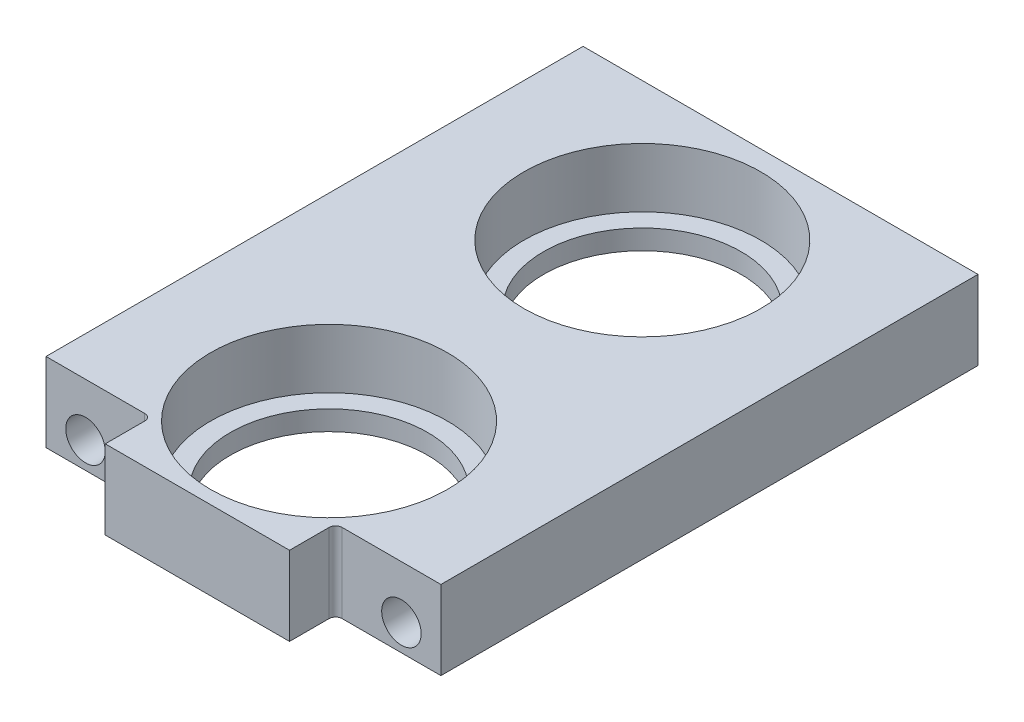
SolidWorks part; units mm, degrees
material "6061 合金"
ref_plane "前视基准面" through (0, 0, 0) normal (0, 0, 1) x (1, 0, 0)
ref_plane "上视基准面" through (0, 0, 0) normal (0, 1, 0) x (1, 0, 0)
ref_plane "右视基准面" through (0, 0, 0) normal (1, 0, 0) x (0, 0, -1)
sketch "草图1" plane through (0, 0, 0) normal (0, 1, 0) x (1, 0, 0)
  line L1 (-15, 22.15) -> (15, 22.15)
  line L2 (-15, 22.15) -> (-15, -22.15)
  line L3 (-15, -22.15) -> (15, -22.15)
  line L4 (15, 22.15) -> (15, -22.15)
  line L5 (-15, 22.15) -> (15, -22.15) construction
  line L6 (-15, -22.15) -> (15, 22.15) construction
  point P0 (0, 0)
  dimension "D1" = 30
  dimension "D2" = 44.3
extrude "凸台-拉伸1" add sketch "草图1" along normal blind 6
sketch "草图2" plane through (0, 6, 0) normal (0, 1, 0) x (1, 0, 0)
  line L0 (0, 22.15) -> (0, -22.15) construction
  line L1 (15, 22.15) -> (-15, 22.15) construction
  line L2 (-15, -22.15) -> (15, -22.15) construction
  circle A0 centre (0, 11.65) radius 9
  circle A1 centre (0, -12.15) radius 9
  dimension "D1" = 18
  dimension "D2" = 10.5
  dimension "D3" = 23.8
extrude "切除-拉伸1" cut sketch "草图2" against normal blind 4.5
sketch "草图3" plane through (0, 1.5, 0) normal (0, 1, 0) x (1, 0, 0)
  circle A0 centre (0, 11.65) radius 7.5
  circle A1 centre (0, -12.15) radius 7.5
  dimension "D1" = 15
extrude "切除-拉伸2" cut sketch "草图3" against normal blind 4.5
sketch "草图5" plane through (0, 6, 0) normal (0, 1, 0) x (1, 0, 0)
  line L0 (0, 0) -> (0, -22.15) construction
  line L1 (-15, -22.15) -> (15, -22.15) construction
  line L2 (-7, -22.15) -> (7, -22.15) construction
  line L3 (7, -22.15) -> (7, -18.65)
  line L4 (7, -18.65) -> (15, -18.65)
  line L5 (15, -22.15) -> (15, 22.15) construction
  line L6 (15, -18.65) -> (15, -22.15)
  line L7 (15, -22.15) -> (7, -22.15)
  line L8 (-15, -18.65) -> (-15, -22.15)
  line L9 (-7, -18.65) -> (-15, -18.65)
  line L10 (-7, -22.15) -> (-7, -18.65)
  line L11 (-15, -22.15) -> (-7, -22.15)
  dimension "D1" = 14
  dimension "D2" = 3.5
extrude "切除-拉伸3" cut sketch "草图5" against normal blind 10
fillet "圆角1" radius 0.5 2 edges at (-7, 3, 18.65) (7, 3, 18.65)
sketch "草图6" plane through (0, 0, 18.65) normal (0, 0, 1) x (1, 0, 0)
  line L0 (-8, 6) -> (-8, 0) construction
  line L1 (-7.5, 6) -> (-15, 6) construction
  line L2 (-7.5, 0) -> (-15, 0) construction
  line L4 (0, 0) -> (0, 6) construction
  circle A0 centre (-12, 2) radius 1.5
  circle A2 centre (12, 2) radius 1.5
  dimension "D3" = 3
  dimension "D1" = 8
  dimension "D2" = 4
  dimension "D4" = 4
extrude "安装打孔" cut sketch "草图6" against normal blind 5
